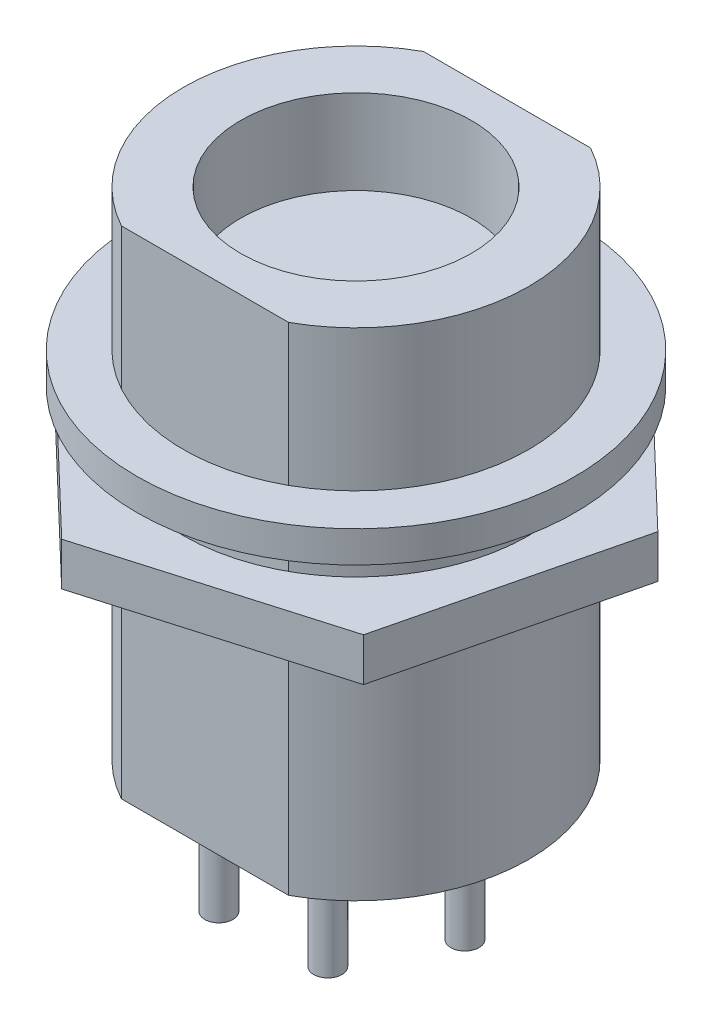
SolidWorks part; units mm, degrees
ref_plane "Front Plane" through (0, 0, 0) normal (0, 0, 1) x (1, 0, 0)
ref_plane "Top Plane" through (0, 0, 0) normal (0, 1, 0) x (1, 0, 0)
ref_plane "Right Plane" through (0, 0, 0) normal (1, 0, 0) x (0, 0, -1)
ref_axis "Axis1" through (0, 0, 0) along (0, 1, 0)
sketch "Sketch1" plane through (0, 0, 0) normal (0, 0, 1) x (1, 0, 0)
  line L0 (0, 0) -> (0, -16617.965) construction
  line L1 (-8, 0) -> (-5.3451, 0)
  line L2 (-5.3451, 0) -> (-5.3451, -3.9242)
  line L3 (-5.3451, -3.9242) -> (0, -3.9242)
  line L4 (0, -3.9242) -> (0, -23)
  line L5 (0, -23) -> (-8, -23)
  line L6 (-8, -23) -> (-8, 0)
  dimension "D1" = 16
  dimension "D2" = 23
revolve "Revolve1" add sketch "Sketch1" angle 360 about L0
sketch "Sketch2" plane through (0, 0, 0) normal (0, 1, 0) x (1, 0, 0)
  line L1 (-13.3173, -7) -> (13.3173, -7)
  line L2 (-13.3173, -7) -> (-13.3173, 7)
  line L3 (-13.3173, 7) -> (13.3173, 7)
  line L4 (13.3173, -7) -> (13.3173, 7)
  line L5 (-13.3173, -7) -> (13.3173, 7) construction
  line L6 (-13.3173, 7) -> (13.3173, -7) construction
  line L7 (-22.1955, -15.0484) -> (22.1955, -15.0484)
  line L8 (-22.1955, -15.0484) -> (-22.1955, 15.0484)
  line L9 (-22.1955, 15.0484) -> (22.1955, 15.0484)
  line L10 (22.1955, -15.0484) -> (22.1955, 15.0484)
  line L11 (-22.1955, -15.0484) -> (22.1955, 15.0484) construction
  line L12 (-22.1955, 15.0484) -> (22.1955, -15.0484) construction
  point P0 (0, 0)
  point P6 (0, 0)
  dimension "D1" = 14
extrude "Cut-Extrude1" cut sketch "Sketch2" against normal through all
sketch "Sketch3" plane through (0, -23, 0) normal (0, -1, 0) x (1, 0, 0)
  circle A0 centre (2.6395, 3.9442) radius 0.6534
extrude "Boss-Extrude1" add sketch "Sketch3" along normal blind 5
pattern_circular "CirPattern1" count 6 over 360 about axis through (0, 0, 0) along (0, 1, 0) of "Boss-Extrude1"
sketch "Sketch5" plane through (0, 0, 0) normal (0, 0, 1) x (1, 0, 0)
  line L0 (-8, 0) -> (-8, -23) construction
  line L1 (-10.1527, -6.5441) -> (-8, -6.5441)
  line L2 (-10.1527, -6.5441) -> (-10.1527, -8)
  line L3 (-10.1527, -8) -> (-8, -8)
  line L4 (-8, -6.5441) -> (-8, -8)
  line L5 (-5.3889, -28) -> (-4.0821, -28) construction
  dimension "D1" = 20
revolve "Revolve2" add sketch "Sketch5" angle 360 about axis through (0, 0, 0) along (0, 1, 0)
sketch "Sketch6" plane through (0, 0, 0) normal (0, 1, 0) x (1, 0, 0)
  line L1 (10.8322, 3.1583) -> (2.6809, 10.9601)
  line L2 (2.6809, 10.9601) -> (-8.1513, 7.8018)
  line L3 (-8.1513, 7.8018) -> (-10.8322, -3.1583)
  line L4 (-10.8322, -3.1583) -> (-2.6809, -10.9601)
  line L5 (-2.6809, -10.9601) -> (8.1513, -7.8018)
  line L6 (8.1513, -7.8018) -> (10.8322, 3.1583)
  circle A0 centre (0, 0) radius 8
  circle A1 centre (0, 0) radius 9.7716 construction
extrude "Boss-Extrude2" add sketch "Sketch6" against normal blind 2 from offset 10 separate body
